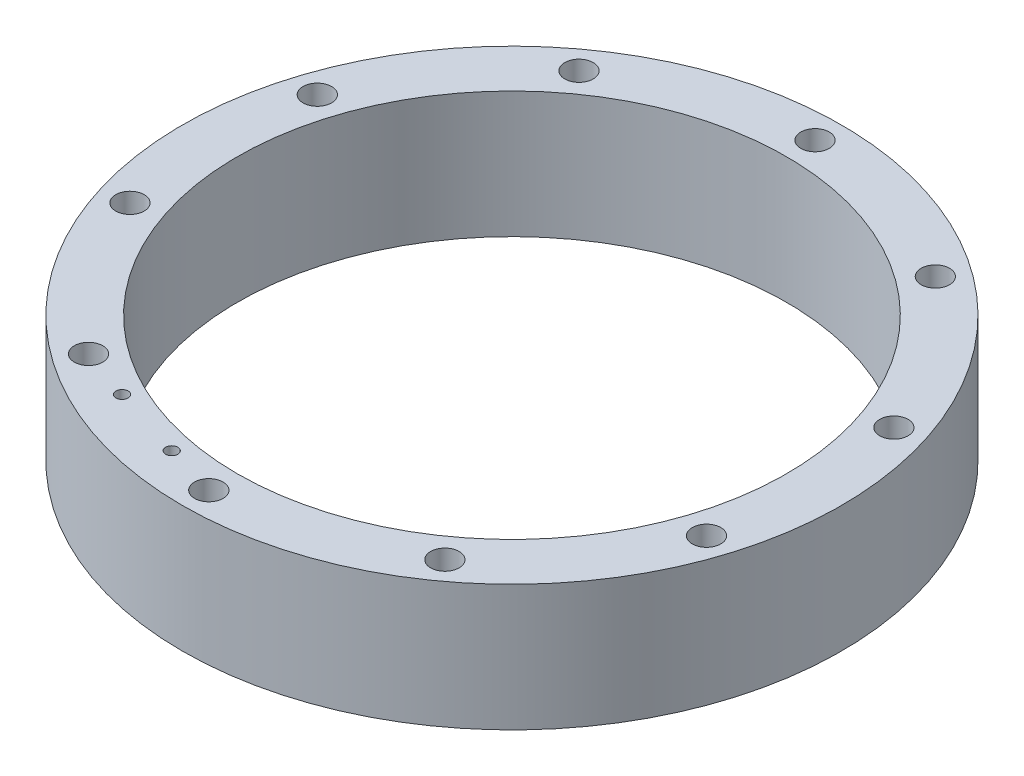
SolidWorks part; units mm, degrees
ref_plane "Front Plane" through (0, 0, 0) normal (0, 0, 1) x (1, 0, 0)
ref_plane "Top Plane" through (0, 0, 0) normal (0, 1, 0) x (1, 0, 0)
ref_plane "Right Plane" through (0, 0, 0) normal (1, 0, 0) x (0, 0, -1)
sketch "Sketch1" plane through (0, 0, 0) normal (0, 1, 0) x (1, 0, 0)
  circle A0 centre (0, 0) radius 40.5
  circle A1 centre (0, 0) radius 37.25 construction
  circle A2 centre (0, 37.25) radius 1.75
  circle A3 centre (21.895, 30.1359) radius 1.75
  circle A4 centre (35.4269, 11.5109) radius 1.75
  circle A5 centre (35.4269, -11.5109) radius 1.75
  circle A6 centre (21.895, -30.1359) radius 1.75
  circle A7 centre (0, -37.25) radius 1.75
  circle A8 centre (-21.895, -30.1359) radius 1.75
  circle A9 centre (-35.4269, -11.5109) radius 1.75
  circle A10 centre (-35.4269, 11.5109) radius 1.75
  circle A11 centre (-21.895, 30.1359) radius 1.75
  circle A12 centre (0, 0) radius 33.75
  point P26 (0, 0)
  dimension "D1" = 81
  dimension "D2" = 74.5
  dimension "D3" = 3.5
  dimension "D5" = 67.5
  dimension "D4" = 10
extrude "Boss-Extrude1" add sketch "Sketch1" along normal blind 15.5
sketch "Sketch2" plane through (0, 15.5, 0) normal (0, 1, 0) x (1, 0, 0)
  line L0 (-21.895, -30.1359) -> (0, -37.25) construction
  line L1 (-6.4835, -35.3254) -> (-15.5185, -32.3898) construction
  line L2 (-11.001, -33.8576) -> (-10.9475, -33.6929) construction
  circle A0 centre (-6.4835, -35.3254) radius 0.75
  circle A1 centre (-15.5185, -32.3898) radius 0.75
  dimension "D1" = 1.5
  dimension "D2" = 0.1731
  dimension "D3" = 9.5
extrude "Cut-Extrude1" cut sketch "Sketch2" against normal through all
